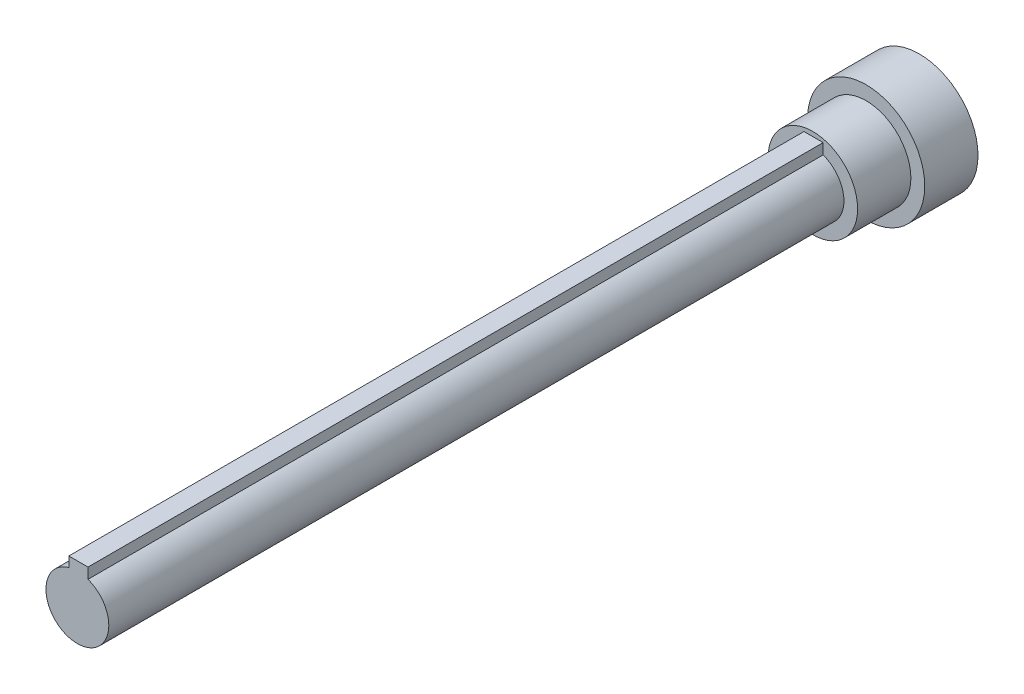
SolidWorks part; units mm, degrees
ref_plane "Front Plane" through (0, 0, 0) normal (1, 0, 0) x (0, 1, 0)
ref_plane "Top Plane" through (0, 0, 0) normal (0, 0, 1) x (0, 1, 0)
ref_plane "Right Plane" through (0, 0, 0) normal (0, 1, 0) x (-1, 0, 0)
sketch "Sketch1" plane through (0, 0, 0) normal (0, 0, 1) x (0, 1, 0)
  circle A0 centre (0, 0) radius 5.5
  dimension "D1" = 11
extrude "Boss-Extrude1" add sketch "Sketch1" along normal blind 5
sketch "Sketch3" plane through (0, 0, 5) normal (0, 0, 1) x (1, 0, 0)
  circle A0 centre (0, 0) radius 4.2
  dimension "D1" = 8.4
extrude "Boss-Extrude3" add sketch "Sketch3" along normal blind 5
sketch "Sketch2" plane through (0, 0, 10) normal (0, 0, 1) x (1, 0, 0)
  line L1 (-0.8342, 3.7759) -> (0.9658, 3.7759)
  line L2 (-0.8342, 3.7759) -> (-0.8342, 2.839)
  line L4 (0.9658, 3.7759) -> (0.9658, 2.7759)
  arc A0 (-0.8342, 2.839) -> (0.9658, 2.7759) centre (-0.0325, 0) ccw
  dimension "D1" = 5.9
  dimension "D3" = 0
  dimension "D2" = 1.8
  dimension "D4" = 1
extrude "Boss-Extrude2" add sketch "Sketch2" along normal blind 69
